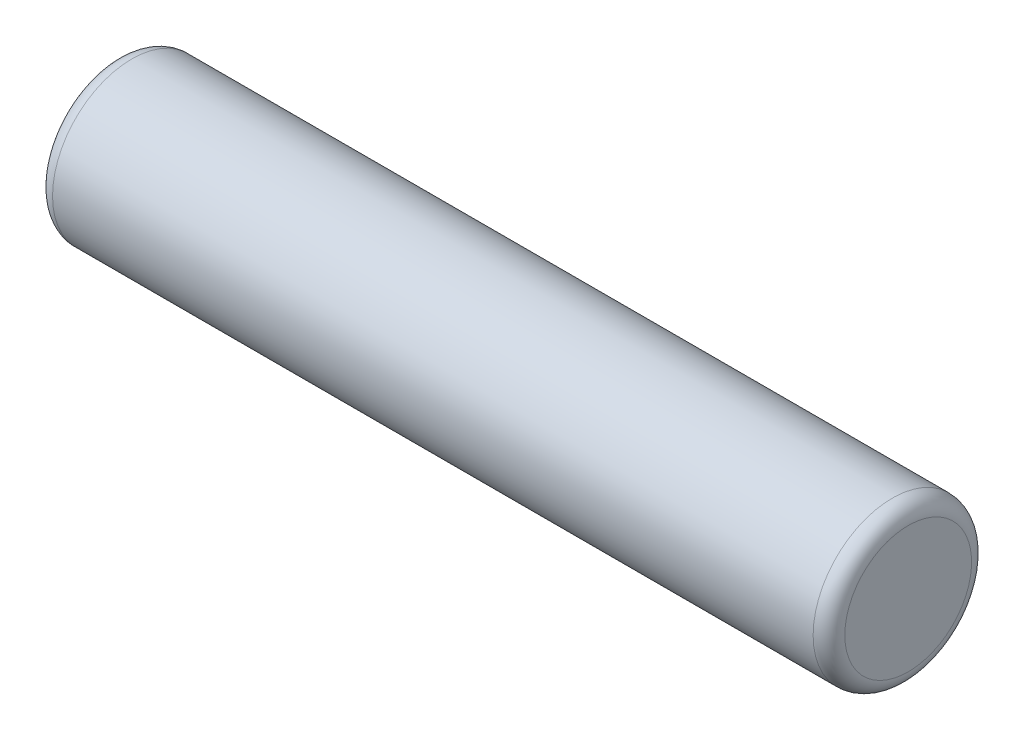
SolidWorks part; units mm, degrees
ref_plane "Ön Düzlem" through (0, 0, 0) normal (0, 0, 1) x (1, 0, 0)
ref_plane "Üst Düzlem" through (0, 0, 0) normal (0, 1, 0) x (1, 0, 0)
ref_plane "Sağ Düzlem" through (0, 0, 0) normal (1, 0, 0) x (0, 0, -1)
sketch "Çizim1" plane through (0, 0, 0) normal (0, 0, 1) x (1, 0, 0)
  line L1 (0, 0) -> (50, 0)
  line L2 (0, 0) -> (0, 5)
  line L3 (0, 5) -> (50, 5)
  line L4 (50, 0) -> (50, 5)
  dimension "D1" = 5
  dimension "D2" = 50
revolve "Döndür1" add sketch "Çizim1" angle 360 about L1
cosmetic thread "Kozmetik Diş Açma1" parameters "D2"=8.619
fillet "Radyus1" radius 1 2 edges at (50, 0, 5) (0, 0, 5)
